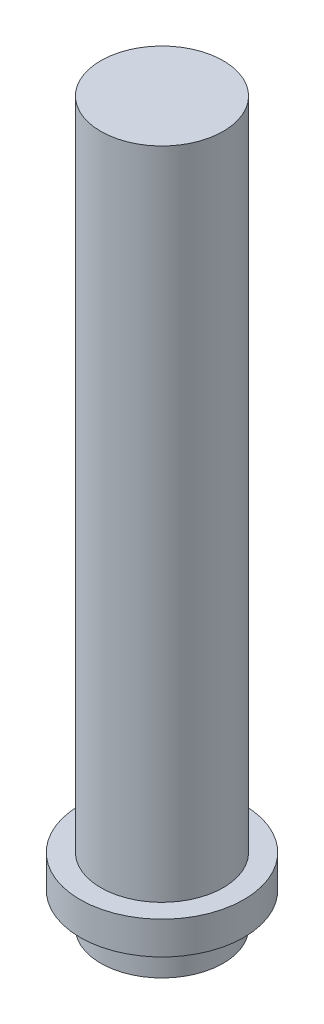
SolidWorks part; units mm, degrees
ref_plane "Front Plane" through (0, 0, 0) normal (0, 0, 1) x (1, 0, 0)
ref_plane "Top Plane" through (0, 0, 0) normal (0, 1, 0) x (1, 0, 0)
ref_plane "Right Plane" through (0, 0, 0) normal (1, 0, 0) x (0, 0, -1)
sketch "Sketch1" plane through (0, 0, 0) normal (0, 1, 0) x (1, 0, 0)
  circle A0 centre (0, 0) radius 6.35
  dimension "D1" = 12.7
extrude "Boss-Extrude1" add sketch "Sketch1" along normal blind 2.54
sketch "Sketch2" plane through (0, 2.54, 0) normal (0, 1, 0) x (1, 0, 0)
  circle A0 centre (0, 0) radius 4.7498
  dimension "D1" = 9.4996
extrude "Boss-Extrude2" add sketch "Sketch2" along normal blind 50.8
sketch "Sketch3" plane through (0, 0, 0) normal (0, -1, 0) x (1, 0, 0)
  circle A0 centre (0, 0) radius 4.7498
  dimension "D1" = 9.4996
extrude "Boss-Extrude3" add sketch "Sketch3" along normal blind 2.54
